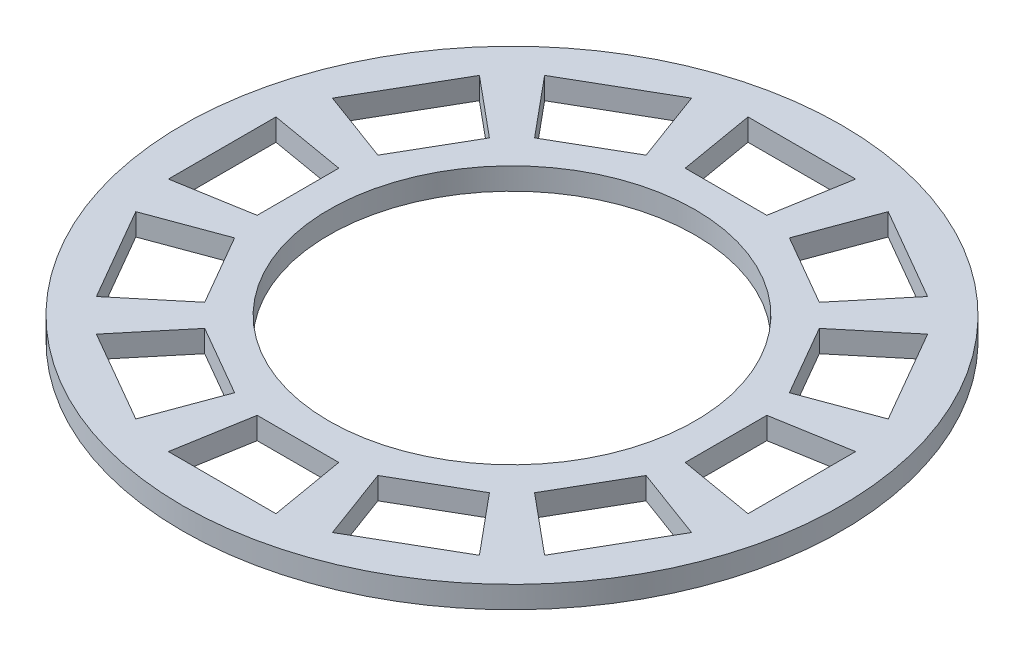
SolidWorks part; units mm, degrees
ref_plane "Front Plane" through (0, 0, 0) normal (0, 0, 1) x (1, 0, 0)
ref_plane "Top Plane" through (0, 0, 0) normal (0, 1, 0) x (1, 0, 0)
ref_plane "Right Plane" through (0, 0, 0) normal (1, 0, 0) x (0, 0, -1)
sketch "Sketch1" plane through (0, 0, 0) normal (0, 1, 0) x (1, 0, 0)
  line L0 (-7.346, 39.574) -> (7.346, 39.574)
  line L1 (7.346, 39.574) -> (5.573, 29.2233)
  line L2 (5.573, 29.2233) -> (-5.573, 29.2233)
  line L3 (-5.573, 29.2233) -> (-7.346, 39.574)
  line L4 (0, -55) -> (0, 55) construction
  line L5 (9.7853, 28.0947) -> (13.4252, 37.9451)
  line L6 (13.4252, 37.9451) -> (26.1488, 30.5991)
  line L7 (26.1488, 30.5991) -> (19.438, 22.5217)
  line L8 (19.438, 22.5217) -> (9.7853, 28.0947)
  line L9 (22.5217, 19.438) -> (30.5991, 26.1488)
  line L10 (30.5991, 26.1488) -> (37.9451, 13.4252)
  line L11 (37.9451, 13.4252) -> (28.0947, 9.7853)
  line L12 (28.0947, 9.7853) -> (22.5217, 19.438)
  line L13 (29.2233, 5.573) -> (39.574, 7.346)
  line L14 (39.574, 7.346) -> (39.574, -7.346)
  line L15 (39.574, -7.346) -> (29.2233, -5.573)
  line L16 (29.2233, -5.573) -> (29.2233, 5.573)
  line L17 (28.0947, -9.7853) -> (37.9451, -13.4252)
  line L18 (37.9451, -13.4252) -> (30.5991, -26.1488)
  line L19 (30.5991, -26.1488) -> (22.5217, -19.438)
  line L20 (22.5217, -19.438) -> (28.0947, -9.7853)
  line L21 (19.438, -22.5217) -> (26.1488, -30.5991)
  line L22 (26.1488, -30.5991) -> (13.4252, -37.9451)
  line L23 (13.4252, -37.9451) -> (9.7853, -28.0947)
  line L24 (9.7853, -28.0947) -> (19.438, -22.5217)
  line L25 (5.573, -29.2233) -> (7.346, -39.574)
  line L26 (7.346, -39.574) -> (-7.346, -39.574)
  line L27 (-7.346, -39.574) -> (-5.573, -29.2233)
  line L28 (-5.573, -29.2233) -> (5.573, -29.2233)
  line L29 (-9.7853, -28.0947) -> (-13.4252, -37.9451)
  line L30 (-13.4252, -37.9451) -> (-26.1488, -30.5991)
  line L31 (-26.1488, -30.5991) -> (-19.438, -22.5217)
  line L32 (-19.438, -22.5217) -> (-9.7853, -28.0947)
  line L33 (-22.5217, -19.438) -> (-30.5991, -26.1488)
  line L34 (-30.5991, -26.1488) -> (-37.9451, -13.4252)
  line L35 (-37.9451, -13.4252) -> (-28.0947, -9.7853)
  line L36 (-28.0947, -9.7853) -> (-22.5217, -19.438)
  line L37 (-29.2233, -5.573) -> (-39.574, -7.346)
  line L38 (-39.574, -7.346) -> (-39.574, 7.346)
  line L39 (-39.574, 7.346) -> (-29.2233, 5.573)
  line L40 (-29.2233, 5.573) -> (-29.2233, -5.573)
  line L41 (-28.0947, 9.7853) -> (-37.9451, 13.4252)
  line L42 (-37.9451, 13.4252) -> (-30.5991, 26.1488)
  line L43 (-30.5991, 26.1488) -> (-22.5217, 19.438)
  line L44 (-22.5217, 19.438) -> (-28.0947, 9.7853)
  line L45 (-19.438, 22.5217) -> (-26.1488, 30.5991)
  line L46 (-26.1488, 30.5991) -> (-13.4252, 37.9451)
  line L47 (-13.4252, 37.9451) -> (-9.7853, 28.0947)
  line L48 (-9.7853, 28.0947) -> (-19.438, 22.5217)
  circle A0 centre (0, 0) radius 40.25
  circle A1 centre (0, 0) radius 29.75
  circle A2 centre (0, 0) radius 45
  circle A3 centre (0, 0) radius 25
  point P15 (0, 39.574)
  dimension "D1" = 80.5
  dimension "D2" = 59.5
  dimension "D3" = 90
  dimension "D4" = 50
  dimension "D5" = 14.692
  dimension "D6" = 11.146
  dimension "D7" = 12
extrude "Boss-Extrude1" add sketch "Sketch1" along normal blind 3 contours A2 | L33 L34 L35 L36 | L37 L38 L39 L40 | L41 L42 L43 L44 | L45 L46 L47 L48 | L3 L0 L1 L2 | L5 L6 L7 L8 | L29 L30 L31 L32 | L25 L26 L27 L28 | L21 L22 L23 L24 | L17 L18 L19 L20 | L13 L14 L15 L16 | L9 L10 L11 L12 | A3
